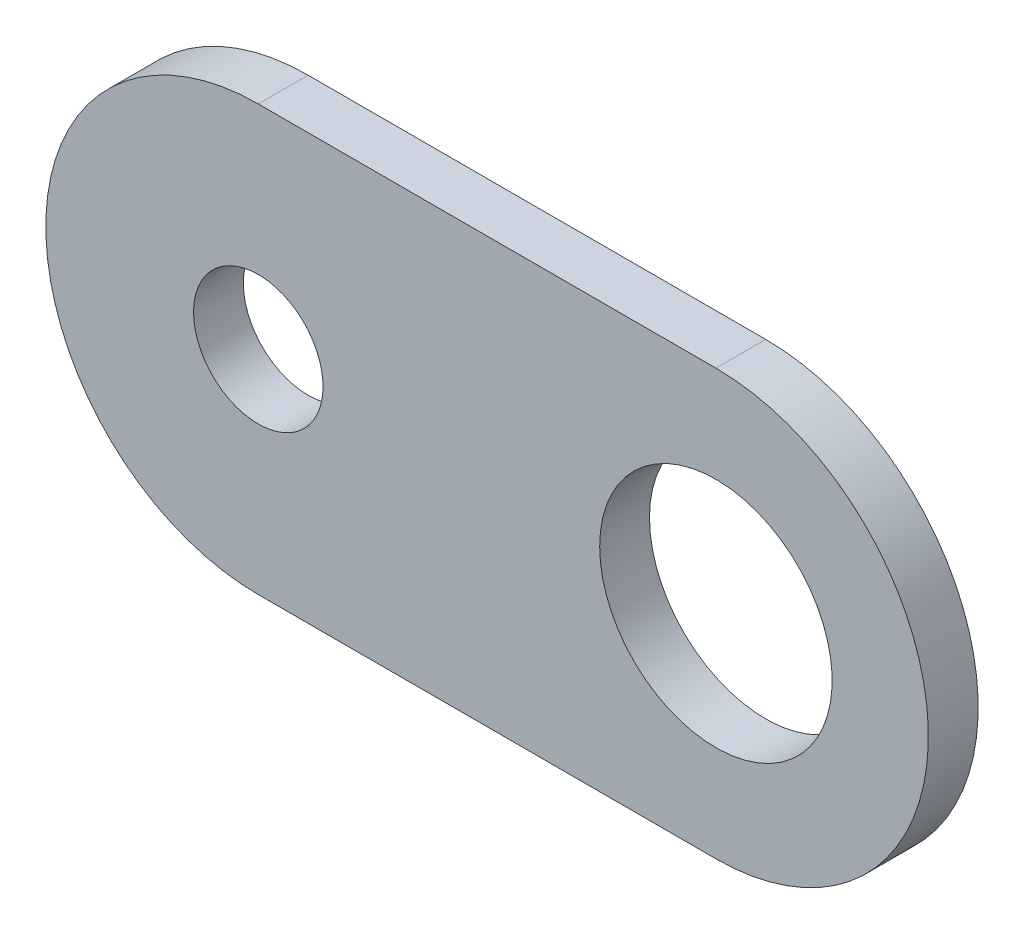
SolidWorks part; units mm, degrees
ref_plane "Front Plane" through (0, 0, 0) normal (0, 0, 1) x (1, 0, 0)
ref_plane "Top Plane" through (0, 0, 0) normal (0, 1, 0) x (1, 0, 0)
ref_plane "Right Plane" through (0, 0, 0) normal (1, 0, 0) x (0, 0, -1)
sketch "Sketch1" plane through (0, 0, 0) normal (0, 0, 1) x (1, 0, 0)
  line L0 (-17.5, 0) -> (0, 0) construction
  line L1 (0, 0) -> (17.5, 0) construction
  line L2 (-17.5, 16.25) -> (17.5, 16.25)
  line L3 (17.5, -16.25) -> (-17.5, -16.25)
  circle A0 centre (-17.5, 0) radius 4.953
  circle A1 centre (17.5, 0) radius 8.89
  arc A2 (17.5, 16.25) -> (17.5, -16.25) centre (17.5, 0) cw
  arc A3 (-17.5, -16.25) -> (-17.5, 16.25) centre (-17.5, 0) cw
  dimension "D2" = 9.906
  dimension "D3" = 17.78
  dimension "D4" = 16.25
  dimension "D1" = 35
extrude "Boss-Extrude1" add sketch "Sketch1" along normal blind 3.81
